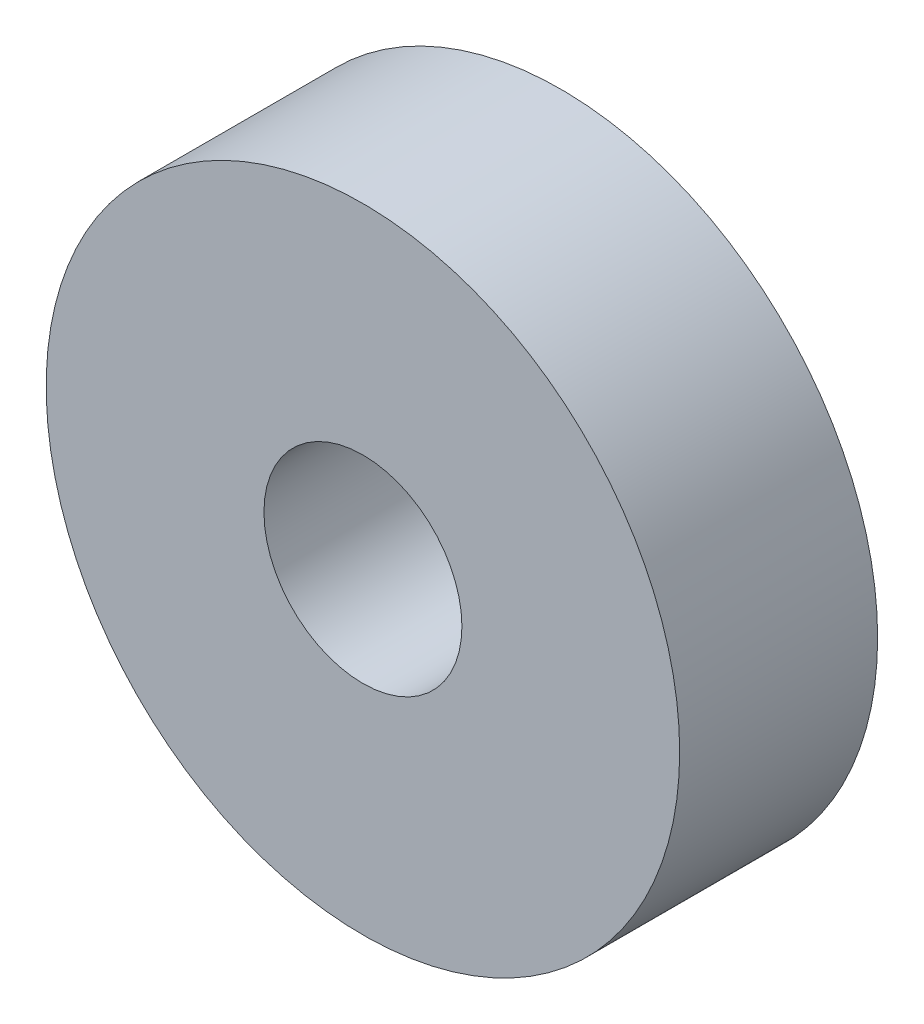
SolidWorks part; units mm, degrees
ref_plane "Plan de face" through (0, 0, 0) normal (0, 0, 1) x (1, 0, 0)
ref_plane "Plan de dessus" through (0, 0, 0) normal (0, 1, 0) x (1, 0, 0)
ref_plane "Plan de droite" through (0, 0, 0) normal (1, 0, 0) x (0, 0, -1)
sketch "Esquisse1" plane through (0, 0, 0) normal (0, 0, 1) x (1, 0, 0)
  circle A0 centre (0, 0) radius 8
  dimension "D1" = 16
extrude "Boss.-Extru.1" add sketch "Esquisse1" along normal blind 5
sketch "Esquisse2" plane through (0, 0, 5) normal (0, 0, 1) x (1, 0, 0)
  circle A0 centre (0, 0) radius 2.5
  dimension "D1" = 5
extrude "Enlèv. mat.-Extru.1" cut sketch "Esquisse2" against normal blind 5
